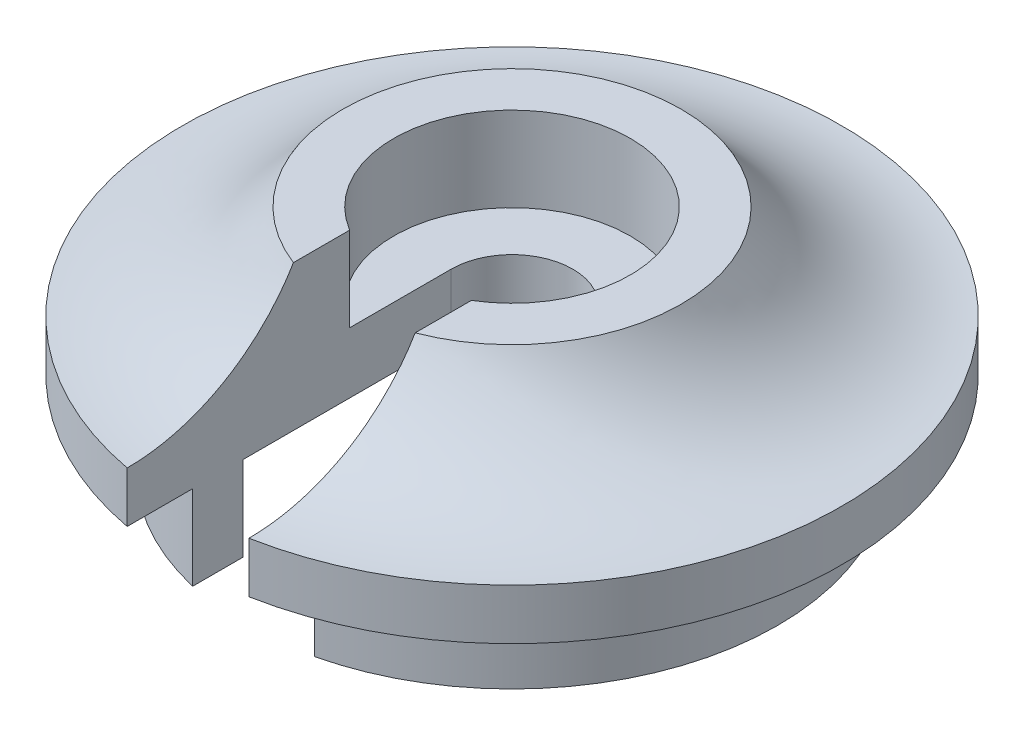
SolidWorks part; units mm, degrees
ref_plane "Piano frontale" through (0, 0, 0) normal (0, 0, 1) x (1, 0, 0)
ref_plane "Piano superiore" through (0, 0, 0) normal (0, 1, 0) x (1, 0, 0)
ref_plane "Piano destro" through (0, 0, 0) normal (1, 0, 0) x (0, 0, -1)
sketch "Schizzo1" plane through (0, 0, 0) normal (0, 0, 1) x (1, 0, 0)
  line L0 (0, 0) -> (-6.415, 0)
  line L1 (-6.415, 0) -> (-6.415, -2.5)
  line L2 (-6.415, -2.5) -> (-7.855, -2.5)
  line L3 (-7.855, -2.5) -> (-7.855, 0)
  line L4 (-7.855, 0) -> (-9.75, 0)
  line L5 (-9.75, 0) -> (-9.75, 1.5)
  line L6 (0, 0) -> (0, 1.8)
  line L7 (0, 1.8) -> (-3.5, 1.8)
  line L8 (-3.5, 1.8) -> (-3.5, 4.3)
  line L9 (-3.5, 4.3) -> (-5, 4.3)
  line L10 (0, -12.4205) -> (0, 16.8729) construction
  arc A0 (-9.75, 1.5) -> (-5, 4.3) centre (-9.75, 6.929) ccw
  dimension "D1" = 15.71
  dimension "D2" = 1.44
  dimension "D3" = 19.5
  dimension "D4" = 6.8
  dimension "D5" = 2.5
  dimension "D6" = 1.5
  dimension "D7" = 2.5
  dimension "D8" = 1.5
  dimension "D9" = 7
revolve "Rivoluzione1" add sketch "Schizzo1" angle 360 about L10
sketch "Schizzo2" plane through (0, 4.3, 0) normal (0, 1, 0) x (1, 0, 0)
  line L0 (-1.8, 0) -> (-1.8, -9.5824)
  line L1 (1.8, 0) -> (1.8, -9.5824)
  circle A0 centre (0, 0) radius 1.8
  circle A1 centre (0, 0) radius 9.75 construction
  circle A2 centre (0, 0) radius 9.75
  circle M1 centre (0, 0) radius 5
  circle M2 centre (0, 0) radius 3.5
  dimension "D1" = 3.6
extrude "Taglio-Estrusione1" cut sketch "Schizzo2" against normal through all contours A0 | L1 L0 M2 M1 | A0 L0 L1 M2 | L0 A2 L1 M1
